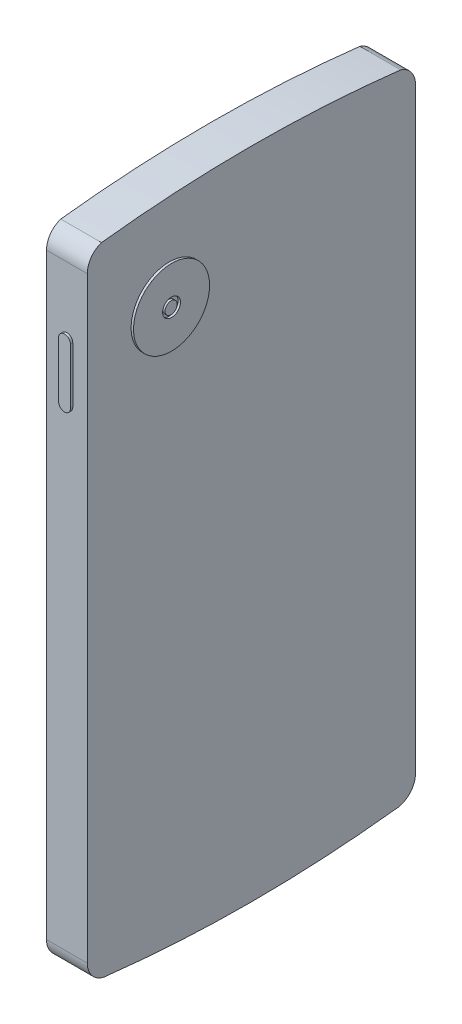
SolidWorks part; units mm, degrees
ref_plane "Plan de face" through (0, 0, 0) normal (0, 0, 1) x (1, 0, 0)
ref_plane "Plan de dessus" through (0, 0, 0) normal (0, 1, 0) x (1, 0, 0)
ref_plane "Plan de droite" through (0, 0, 0) normal (1, 0, 0) x (0, 0, -1)
sketch "Esquisse1" plane through (0, 0, 0) normal (1, 0, 0) x (0, 0, -1)
  line L0 (0, 0) -> (0, 137.84) construction
  line L1 (0, 137.84) -> (-69.17, 137.84) construction
  line L2 (-69.17, 137.84) -> (-69.17, 0) construction
  line L3 (-69.17, 0) -> (0, 0) construction
  line L4 (-69.17, 137.84) -> (-69.17, 131.84)
  line L5 (-69.17, 0) -> (-69.17, 6.0048)
  line L6 (0, 136.0077) -> (0, 131.797)
  line L7 (-69.17, 131.84) -> (-69.17, 6.0048)
  line L8 (0, 131.797) -> (0, 6.0048)
  arc A0 (-69.17, 131.84) -> (-66.1721, 136.0077) centre (-64.7741, 131.84) cw
  arc A1 (0, 131.797) -> (-3.1334, 136.0077) centre (-4.3959, 131.797) ccw
  arc A2 (-66.1721, 136.0077) -> (-3.1334, 136.0077) centre (-34.6527, -134.1732) cw
  arc A3 (0, 6.0048) -> (-4.3959, 1.6089) centre (-4.3959, 6.0048) cw
  arc A4 (-64.7741, 1.6089) -> (-69.17, 6.0048) centre (-64.7741, 6.0048) cw
  arc A5 (-64.7741, 1.6089) -> (-4.3959, 1.6089) centre (-34.585, 263.8102) ccw
  dimension "D1" = 137.84
  dimension "D2" = 69.17
  dimension "D3" = 6
extrude "Boss.-Extru.2" add sketch "Esquisse1" along normal blind 8.59 contours A4 A5 A3 L8 A1 A2 A0 L7
sketch "Esquisse2" plane through (0, 0, 0) normal (-1, 0, 0) x (0, 0, 1)
  line L0 (34.585, -0.1233) -> (34.585, 14.8767) construction
  line L1 (34.6527, 137.84) -> (34.6527, 122.84) construction
  line L2 (34.6527, 122.84) -> (34.585, 14.8767) construction
  line L4 (1.6694, 122.84) -> (67.5683, 122.84)
  line L5 (1.6694, 122.84) -> (1.6694, 14.8767)
  line L6 (1.6694, 14.8767) -> (67.5683, 14.8767)
  line L7 (67.5683, 122.84) -> (67.5683, 14.8767)
  line L8 (1.6694, 122.84) -> (67.5683, 14.8767) construction
  line L9 (1.6694, 14.8767) -> (67.5683, 122.84) construction
  arc A0 (4.3959, 1.6089) -> (64.7741, 1.6089) centre (34.585, 263.8102) ccw construction
  arc A1 (66.1721, 136.0077) -> (3.1334, 136.0077) centre (34.6527, -134.1732) ccw construction
  point P12 (34.6189, 68.8583)
  dimension "D1" = 15
  dimension "D2" = 15
extrude "Enlèv. mat.-Extru.1" cut sketch "Esquisse2" against normal blind 0.005
sketch "Esquisse3" plane through (0, 0, 0) normal (-1, 0, 0) x (0, 0, 1)
  line L0 (34.6527, 137.84) -> (34.6189, 122.84) construction
  line L1 (67.5683, 122.84) -> (1.6694, 122.84) construction
  arc A0 (66.1721, 136.0077) -> (3.1334, 136.0077) centre (34.6527, -134.1732) ccw construction
  circle A1 centre (34.633, 129.1308) radius 2.4121
extrude "Enlèv. mat.-Extru.2" cut sketch "Esquisse3" against normal blind 0.005
sketch "Esquisse4" plane through (0.005, 0, 0) normal (-1, 0, 0) x (0, 0, 1)
  line L0 (34.633, 131.543) -> (34.633, 126.7187) construction
  line L1 (32.2209, 129.1308) -> (37.0452, 129.1308) construction
  line L2 (34.633, 129.1308) -> (32.9274, 130.8365) construction
  line L3 (32.9274, 130.8365) -> (36.3387, 127.4252) construction
  line L4 (36.3387, 127.4252) -> (36.3387, 130.8365) construction
  line L5 (36.3387, 130.8365) -> (32.9274, 130.8365) construction
  line L6 (32.9274, 130.8365) -> (32.9274, 127.4252) construction
  line L7 (32.9274, 127.4252) -> (36.3387, 127.4252) construction
  circle A0 centre (34.633, 129.1308) radius 2.4121 construction
  circle A1 centre (36.7263, 129.1308) radius 0.1929
  circle A2 centre (36.5671, 128.3285) radius 0.1929
  circle A3 centre (36.1129, 127.6483) radius 0.1929
  circle A4 centre (35.433, 127.1936) radius 0.1929
  circle A5 centre (34.6308, 127.0337) radius 0.1929
  circle A6 centre (33.8285, 127.1929) radius 0.1929
  circle A7 centre (33.1483, 127.6471) radius 0.1929
  circle A8 centre (32.6936, 128.327) radius 0.1929
  circle A9 centre (32.5337, 129.1292) radius 0.1929
  circle A10 centre (32.6929, 129.9315) radius 0.1929
  circle A11 centre (33.1471, 130.6117) radius 0.1929
  circle A12 centre (33.827, 131.0664) radius 0.1929
  circle A13 centre (34.6292, 131.2263) radius 0.1929
  circle A14 centre (35.4315, 131.0671) radius 0.1929
  circle A15 centre (36.1117, 130.6129) radius 0.1929
  circle A16 centre (36.5664, 129.933) radius 0.1929
  circle A17 centre (36.1117, 129.1308) radius 0.1929
  circle A18 centre (35.4315, 129.1308) radius 0.1929
  circle A19 centre (34.633, 129.1308) radius 0.1929
  circle A20 centre (35.9108, 128.3808) radius 0.1929
  circle A21 centre (35.3617, 127.8318) radius 0.1929
  circle A22 centre (34.6117, 127.6308) radius 0.1929
  circle A23 centre (33.8617, 127.8318) radius 0.1929
  circle A24 centre (33.3127, 128.3808) radius 0.1929
  circle A25 centre (33.1117, 129.1308) radius 0.1929
  circle A26 centre (33.3127, 129.8808) radius 0.1929
  circle A27 centre (33.8617, 130.4299) radius 0.1929
  circle A28 centre (34.6117, 130.6308) radius 0.1929
  circle A29 centre (35.3617, 130.4299) radius 0.1929
  circle A30 centre (35.9108, 129.8808) radius 0.1929
  circle A31 centre (35.1679, 128.4944) radius 0.1929
  circle A32 centre (34.5315, 128.2308) radius 0.1929
  circle A33 centre (33.8951, 128.4944) radius 0.1929
  circle A34 centre (33.6315, 129.1308) radius 0.1929
  circle A35 centre (33.8951, 129.7672) radius 0.1929
  circle A36 centre (34.5315, 130.0308) radius 0.1929
  circle A37 centre (35.1679, 129.7672) radius 0.1929
  point P46 (34.63, 129.13)
  point P75 (34.6117, 129.1308)
  point P89 (34.5315, 129.1308)
  dimension "D1" = 16
  dimension "D2" = 12
  dimension "D3" = 8
extrude "Enlèv. mat.-Extru.3" cut sketch "Esquisse4" against normal blind 0.005
sketch "Esquisse5" plane through (0, 0, 0) normal (-1, 0, 0) x (0, 0, 1)
  line L0 (15.3735, 137.1559) -> (15.3735, 127.1567) construction
  arc A0 (66.1721, 136.0077) -> (3.1334, 136.0077) centre (34.6527, -134.1732) ccw construction
  circle A1 centre (15.3735, 128.9685) radius 1.4387
extrude "Enlèv. mat.-Extru.4" cut sketch "Esquisse5" against normal blind 0.05 draft 83
sketch "Esquisse6" plane through (8.59, 0, 0) normal (1, 0, 0) x (0, 0, -1)
  line L0 (-34.6527, 137.84) -> (-34.6527, 96.8085) construction
  line L1 (-34.6527, 96.8085) -> (-34.6527, 117.3243) construction
  line L2 (-34.6527, 117.3243) -> (-69.17, 117.3243) construction
  line L3 (-69.17, 131.84) -> (-69.17, 6.0048) construction
  line L4 (-59.9255, 117.3243) -> (-51.9114, 117.3243) construction
  line L5 (-51.9114, 117.3243) -> (-43.8972, 117.3243) construction
  arc A0 (-3.1334, 136.0077) -> (-66.1721, 136.0077) centre (-34.6527, -134.1732) ccw construction
  circle A1 centre (-51.9114, 117.3243) radius 8.0142
  circle A2 centre (-51.9114, 117.3243) radius 1.8784
extrude "Boss.-Extru.4" add sketch "Esquisse6" along normal blind 0.5 separate body
sketch "Esquisse9" plane through (8.59, 0, 0) normal (1, 0, 0) x (0, 0, -1)
  circle A0 centre (-52.0126, 117.2863) radius 1.2723
extrude "Boss.-Extru.6" add sketch "Esquisse9" along normal blind 0.5 separate body
sketch "Esquisse10" plane through (0, 0, 0) normal (0, 0, -1) x (-1, 0, 0)
  line L0 (-8.59, 113.3671) -> (0, 113.3671) construction
  line L1 (-8.59, 131.797) -> (-8.59, 6.0048) construction
  line L2 (0, 131.797) -> (0, 6.0048) construction
  line L3 (-4.295, 113.3671) -> (-4.295, 94.7812) construction
  line L4 (-3.275, 113.3671) -> (-3.275, 94.7812)
  line L5 (-5.315, 113.3671) -> (-5.315, 94.7812)
  arc A0 (-3.275, 113.3671) -> (-5.315, 113.3671) centre (-4.295, 113.3671) ccw
  arc A1 (-5.315, 94.7812) -> (-3.275, 94.7812) centre (-4.295, 94.7812) ccw
  point P8 (-4.295, 104.0742)
extrude "Boss.-Extru.7" add sketch "Esquisse10" along normal blind 0.5
sketch "Esquisse11" plane through (0, 0, 69.17) normal (0, 0, 1) x (1, 0, 0)
  line L0 (0, 111.8107) -> (8.59, 111.8107) construction
  line L1 (0, 131.84) -> (0, 6.0048) construction
  line L2 (8.59, 131.84) -> (8.59, 6.0048) construction
  line L3 (4.295, 117.6885) -> (4.295, 105.9328) construction
  line L4 (5.5352, 117.6885) -> (5.5352, 105.9328)
  line L5 (3.0548, 117.6885) -> (3.0548, 105.9328)
  arc A0 (5.5352, 117.6885) -> (3.0548, 117.6885) centre (4.295, 117.6885) ccw
  arc A1 (3.0548, 105.9328) -> (5.5352, 105.9328) centre (4.295, 105.9328) ccw
  point P8 (4.295, 111.8107)
extrude "Boss.-Extru.8" add sketch "Esquisse11" along normal blind 0.5
